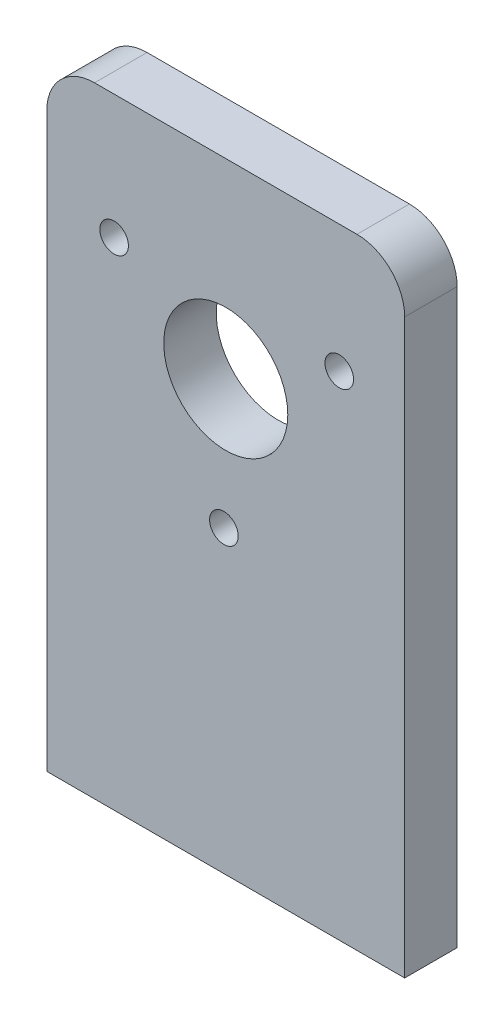
SolidWorks part; units mm, degrees
ref_plane "Front Plane" through (0, 0, 0) normal (0, 0, 1) x (1, 0, 0)
ref_plane "Top Plane" through (0, 0, 0) normal (0, 1, 0) x (1, 0, 0)
ref_plane "Right Plane" through (0, 0, 0) normal (1, 0, 0) x (0, 0, -1)
sketch "Sketch2" plane through (0, 0, 0) normal (0, 0, 1) x (1, 0, 0)
  line L0 (37.5, 0) -> (37.5, 90) construction
  line L1 (0, 0) -> (75, 0)
  line L2 (0, 0) -> (0, 120)
  line L3 (10, 130) -> (65, 130)
  line L4 (75, 0) -> (75, 120)
  line L5 (37.5, 90) -> (61.2914, 90) construction
  line L6 (61.2914, 0) -> (61.2914, 103.2864) construction
  line L7 (37.5, 90) -> (14.0979, 90) construction
  line L8 (37.5, 90) -> (32.5, 90) construction
  line L9 (14.0979, 0) -> (14.0979, 103.9608) construction
  line L11 (32.9745, 0) -> (37.1107, 62.7528) construction
  circle A0 centre (37.5, 90) radius 13
  circle A1 centre (61.2914, 103.2864) radius 3
  circle A2 centre (14.0979, 103.9608) radius 3
  circle A3 centre (37.1107, 62.7528) radius 3
  arc A5 (75, 120) -> (65, 130) centre (65, 120) ccw
  arc A6 (0, 120) -> (10, 130) centre (10, 120) cw
  point P22 (75, 130)
  point P25 (0, 130)
  point P26 (0, 0)
  point P27 (61.2914, 103.2864)
  point P29 (37.1107, 62.7528)
  point P31 (14.0979, 103.9608)
  dimension "D3" = 26
  dimension "D4" = 10
  dimension "D5" = 6
  dimension "D1" = 130
  dimension "D2" = 75
extrude "Boss-Extrude1" add sketch "Sketch2" along normal blind 11
